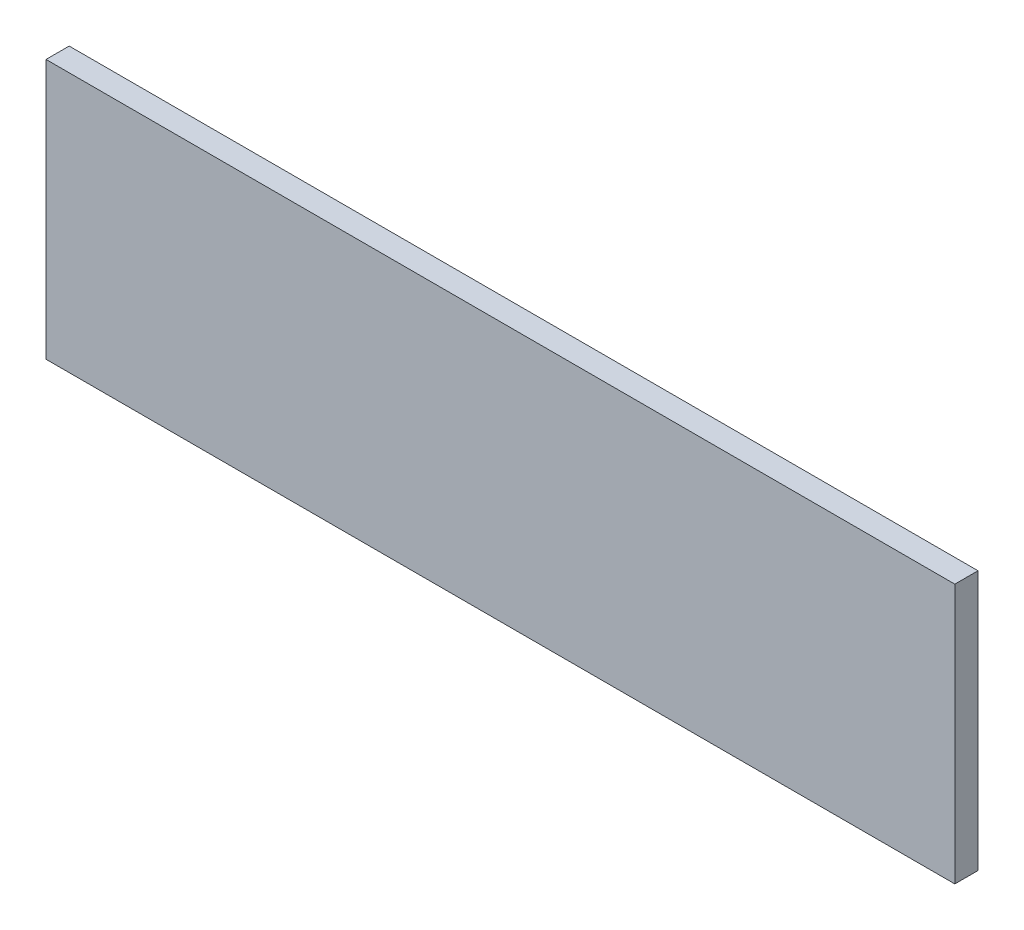
SolidWorks part; units mm, degrees
ref_plane "Front Plane" through (0, 0, 0) normal (1, 0, 0) x (0, 1, 0)
ref_plane "Top Plane" through (0, 0, 0) normal (0, 0, 1) x (0, 1, 0)
ref_plane "Right Plane" through (0, 0, 0) normal (0, 1, 0) x (-1, 0, 0)
sketch "Sketch1" plane through (0, 0, 0) normal (1, 0, 0) x (0, 1, 0)
  line L1 (0, 0) -> (71.12, 0)
  line L2 (0, 0) -> (0, 6.35)
  line L3 (0, 6.35) -> (71.12, 6.35)
  line L4 (71.12, 0) -> (71.12, 6.35)
  dimension "D1" = 71.12
  dimension "D2" = 6.35
extrude "Boss-Extrude1" add sketch "Sketch1" along normal blind 248.92
